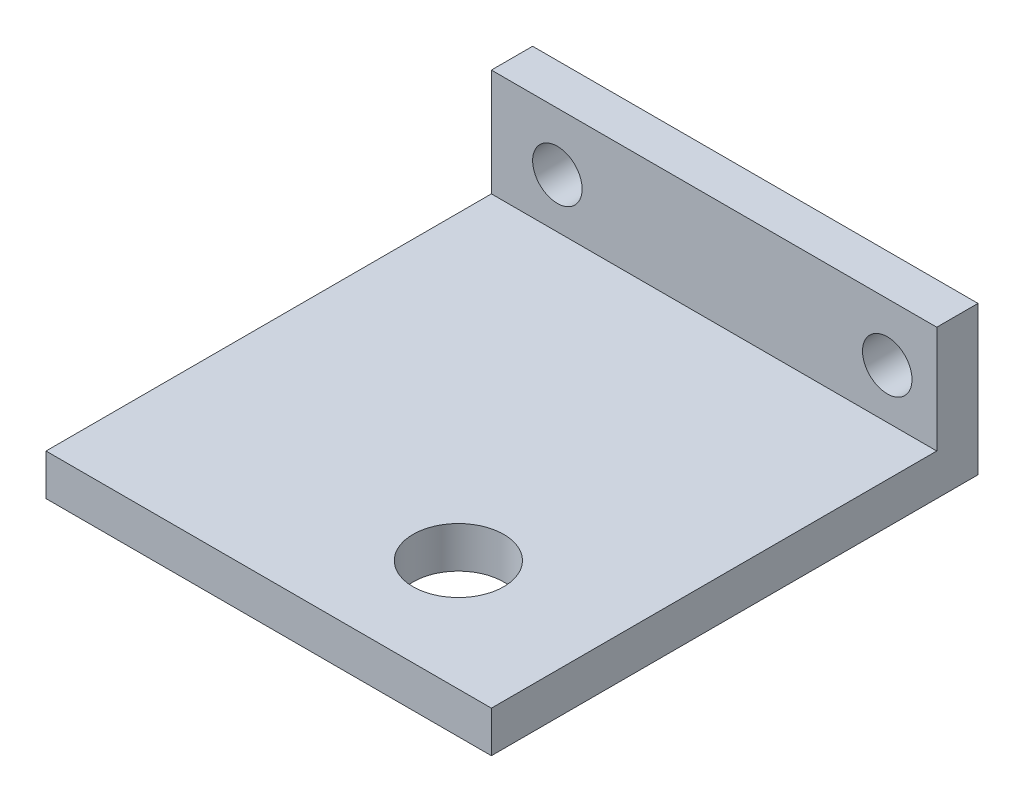
SolidWorks part; units mm, degrees
ref_plane "Plan de face" through (0, 0, 0) normal (0, 0, 1) x (1, 0, 0)
ref_plane "Plan de dessus" through (0, 0, 0) normal (0, 1, 0) x (1, 0, 0)
ref_plane "Plan de droite" through (0, 0, 0) normal (1, 0, 0) x (0, 0, -1)
sketch "Esquisse1" plane through (0, 0, 0) normal (0, 0, 1) x (1, 0, 0)
  line L1 (-27, -9) -> (27, -9)
  line L2 (-27, -9) -> (-27, 9)
  line L3 (-27, 9) -> (27, 9)
  line L4 (27, -9) -> (27, 9)
  line L5 (-27, -9) -> (27, 9) construction
  line L6 (-27, 9) -> (27, -9) construction
  circle A0 centre (-19, 2) radius 3
  circle A1 centre (21, 2) radius 3
  point P0 (0, 0)
  dimension "D3" = 6
  dimension "D1" = 54
  dimension "D2" = 18
  dimension "D4" = 7
  dimension "D5" = 8
  dimension "D6" = 2
extrude "Boss.-Extru.1" add sketch "Esquisse1" along normal blind 59
sketch "Esquisse2" plane through (0, 9, 0) normal (0, 1, 0) x (1, 0, 0)
  line L8 (22, -5) -> (-22, -5)
  line L9 (-22, -5) -> (-22, -54)
  line L10 (-22, -54) -> (22, -54)
  line L11 (22, -54) -> (22, -5)
  line L12 (42.5059, -5) -> (-47.38, -5)
  line L13 (-47.38, -5) -> (-47.38, -79.5648)
  line L14 (-47.38, -79.5648) -> (42.5059, -79.5648)
  line L15 (42.5059, -79.5648) -> (42.5059, -5)
  dimension "D1" = 5
extrude "Enlèv. mat.-Extru.1" cut sketch "Esquisse2" against normal blind 13
hole_wizard "Dégagement M101" positions "Esquisse4" profile "Esquisse3" hole size "M10" standard "JIS" end condition through all
sketch "Esquisse4" plane through (0, -4, 0) normal (0, 1, 0) x (1, 0, 0)
  point P0 (9.5, -45.5022)
sketch "Esquisse3" plane through (9.5, -4, 45.5022) normal (1, 0, 0) x (0, 0, 1)
  line L0 (0, 0) -> (0, 5)
  line L1 (0, 5) -> (5.5, 5)
  line L2 (5.5, 5) -> (5.5, 0)
  line L5 (5.5, 0) -> (0, 0)
  line L11 (0, -6.35) -> (0, 107.95) construction
  dimension "Diamètre du perçage jusqu'au prochain" = 11
  dimension "Profondeur du perçage jusqu'au prochain" = 5
